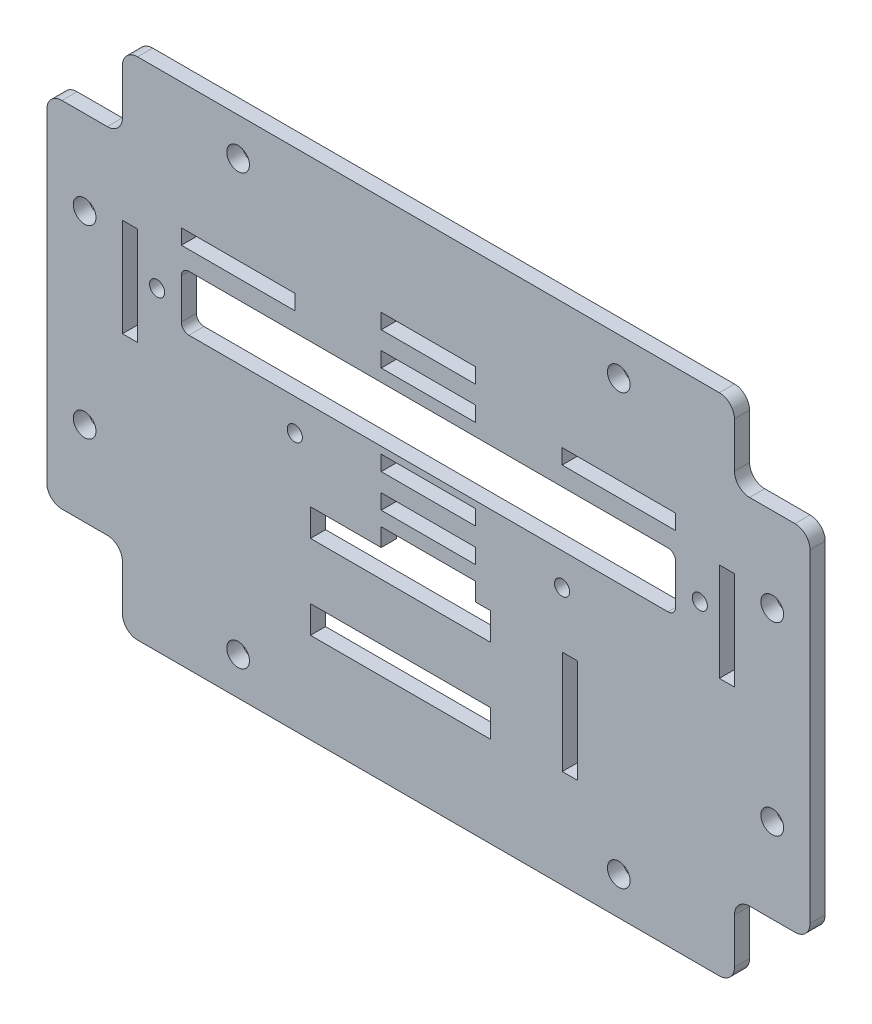
SolidWorks part; units mm, degrees
ref_plane "Front Plane" through (0, 0, 0) normal (0, 0, 1) x (1, 0, 0)
ref_plane "Top Plane" through (0, 0, 0) normal (0, 1, 0) x (1, 0, 0)
ref_plane "Right Plane" through (0, 0, 0) normal (1, 0, 0) x (0, 0, -1)
sketch "Sketch1" plane through (0, 0, 0) normal (0, 0, 1) x (1, 0, 0)
  line L0 (-62.6042, 95.0688) -> (-30.8542, 95.0688)
  line L1 (-30.8542, 95.0688) -> (-30.8542, 100.1488)
  line L2 (-30.8542, 100.1488) -> (-62.6042, 100.1488)
  line L3 (-62.6042, 100.1488) -> (-62.6042, 95.0688)
  line L4 (-62.6042, 106.3017) -> (-30.8542, 106.3017)
  line L5 (-30.8542, 106.3017) -> (-30.8542, 111.3817)
  line L6 (-91.6322, 138.6009) -> (-129.7322, 138.6009)
  line L7 (-144.4697, 135.9652) -> (-144.4697, 127.1956)
  line L8 (-30.8542, 111.3817) -> (-62.6042, 111.3817)
  line L9 (-62.6042, 111.3817) -> (-62.6042, 106.3017)
  line L10 (-62.6042, 141.5187) -> (-62.6042, 136.4387)
  line L11 (-62.6042, 136.4387) -> (-30.8542, 136.4387)
  line L12 (-30.8542, 136.4387) -> (-30.8542, 141.5187)
  line L13 (-162.2497, 132.2748) -> (-162.2497, 94.1323) construction
  line L14 (68.7913, 132.2748) -> (68.7913, 94.1323) construction
  line L15 (-30.8542, 141.5187) -> (-62.6042, 141.5187)
  line L16 (-62.6042, 141.5187) -> (-62.635, 141.5089)
  line L17 (-30.8542, 147.5723) -> (-30.8542, 152.6523)
  line L18 (-75.4947, 173.3689) -> (18.6564, 173.3689) construction
  line L19 (-30.8542, 152.6523) -> (-62.6042, 152.6523)
  line L20 (-1.7677, 84.197) -> (-1.7677, 49.4424)
  line L21 (-62.6042, 152.6523) -> (-62.6042, 147.5723)
  line L22 (-62.6042, 147.5723) -> (-30.8542, 147.5723)
  line L23 (56.0913, 21.4353) -> (56.0913, 36.6753)
  line L24 (-149.5497, 21.4353) -> (-149.5497, 36.6753)
  line L25 (-154.6297, 41.7553) -> (-169.8697, 41.7553)
  line L26 (-144.4697, 186.0689) -> (51.0113, 186.0689)
  line L27 (36.3077, 129.7348) -> (36.3077, 127.1956)
  line L28 (61.1713, 41.7553) -> (76.4113, 41.7553)
  line L29 (81.4913, 101.2121) -> (41.9257, 101.2121) construction
  line L30 (61.1713, 160.6689) -> (76.4113, 160.6689)
  line L31 (56.0913, 180.9889) -> (56.0913, 165.7489)
  line L32 (-25.9222, 49.7003) -> (-25.9222, 55.9976)
  line L33 (33.7677, 132.2748) -> (-127.2261, 132.2748)
  line L34 (-129.7661, 129.7348) -> (-129.7661, 127.1956)
  line L35 (33.7677, 113.6867) -> (-127.2261, 113.6867)
  line L36 (-1.7677, 84.197) -> (3.3123, 84.197)
  line L37 (-149.5497, 180.9889) -> (-149.5497, 165.7489)
  line L38 (-154.6297, 160.6689) -> (-169.8697, 160.6689)
  line L39 (-75.4947, 29.0553) -> (18.6564, 29.0553) construction
  line L40 (-174.9497, 101.2121) -> (-169.8697, 101.2121) construction
  line L41 (-25.9222, 55.9976) -> (-86.3722, 55.9976)
  line L42 (-86.3722, 55.9976) -> (-86.3722, 46.7813)
  line L43 (-86.3722, 46.7813) -> (-25.9222, 46.7813)
  line L44 (-25.9222, 46.7813) -> (-25.9222, 49.7003)
  line L45 (-25.9222, 77.8997) -> (-25.9222, 84.197)
  line L46 (-25.9222, 84.197) -> (-30.8542, 84.197)
  line L47 (-86.3722, 84.197) -> (-86.3722, 74.9807)
  line L48 (-86.3722, 74.9807) -> (-25.9222, 74.9807)
  line L49 (-25.9222, 74.9807) -> (-25.9222, 77.8997)
  line L50 (-62.6042, 84.197) -> (-86.3722, 84.197)
  line L51 (51.0113, 135.9652) -> (51.0113, 127.1956)
  line L52 (-1.8261, 138.6009) -> (36.2739, 138.6009)
  line L54 (-62.6042, 84.197) -> (-62.6042, 90.2559)
  line L55 (-62.6042, 90.2559) -> (-30.8542, 90.2559)
  line L56 (-91.6322, 138.6009) -> (-91.6322, 143.6809)
  line L57 (-129.7322, 138.6009) -> (-129.7322, 143.6809)
  line L58 (-46.7292, 155.5889) -> (-46.7292, 153.1054) construction
  line L59 (-1.8261, 138.6009) -> (-1.8261, 143.6809)
  line L60 (36.2739, 138.6009) -> (36.2739, 143.6809)
  line L61 (-30.8542, 84.197) -> (-30.8542, 90.2559)
  line L66 (-149.5497, 135.9652) -> (-144.4697, 135.9652)
  line L69 (-149.5497, 102.9452) -> (-144.4697, 102.9452)
  line L70 (56.0913, 102.9452) -> (51.0113, 102.9452)
  line L71 (56.0913, 135.9652) -> (51.0113, 135.9652)
  line L72 (-174.9497, 155.5889) -> (-174.9497, 46.8353)
  line L77 (-149.5497, 135.9652) -> (-149.5497, 102.9452)
  line L79 (-129.7322, 143.6809) -> (-91.6322, 143.6809)
  line L80 (-1.7677, 49.4424) -> (3.3123, 49.4424)
  line L82 (-147.6829, 127.1956) -> (60.3007, 127.1956) construction
  line L89 (-1.8261, 143.6809) -> (36.2739, 143.6809)
  line L90 (-144.4697, 127.1956) -> (-144.4697, 102.9452)
  line L91 (-129.7661, 127.1956) -> (-129.7661, 116.2267)
  line L92 (36.3077, 127.1956) -> (36.3077, 116.2267)
  line L93 (51.0113, 127.1956) -> (51.0113, 102.9452)
  line L94 (56.0913, 135.9652) -> (56.0913, 102.9452)
  line L95 (3.3123, 84.197) -> (3.3123, 49.4424)
  line L96 (-144.4697, 16.3553) -> (51.0113, 16.3553)
  line L97 (81.4913, 155.5889) -> (81.4913, 46.8353)
  arc A0 (36.3077, 129.7348) -> (33.7677, 132.2748) centre (33.7677, 129.7348) ccw
  arc A1 (36.3077, 116.2267) -> (33.7677, 113.6867) centre (33.7677, 116.2267) cw
  circle A2 centre (-110.6822, 173.3689) radius 3.81
  circle A3 centre (17.2239, 173.3689) radius 3.81
  arc A4 (-149.5497, 21.4353) -> (-144.4697, 16.3553) centre (-144.4697, 21.4353) ccw
  arc A5 (-169.8697, 41.7553) -> (-174.9497, 46.8353) centre (-169.8697, 46.8353) cw
  arc A6 (-154.6297, 41.7553) -> (-149.5497, 36.6753) centre (-154.6297, 36.6753) cw
  circle A7 centre (-110.6822, 29.0553) radius 3.81
  circle A8 centre (17.2239, 29.0553) radius 3.81
  arc A9 (-127.2261, 113.6867) -> (-129.7661, 116.2267) centre (-127.2261, 116.2267) cw
  arc A10 (-127.2261, 132.2748) -> (-129.7661, 129.7348) centre (-127.2261, 129.7348) ccw
  arc A11 (56.0913, 21.4353) -> (51.0113, 16.3553) centre (51.0113, 21.4353) cw
  circle A12 centre (-162.2497, 132.2748) radius 3.81
  circle A13 centre (-137.9037, 121.9952) radius 2.54
  circle A14 centre (44.4453, 121.9952) radius 2.54
  circle A15 centre (-91.6322, 102.9452) radius 2.54
  circle A16 centre (-1.8261, 102.9452) radius 2.54
  arc A17 (61.1713, 41.7553) -> (56.0913, 36.6753) centre (61.1713, 36.6753) ccw
  arc A18 (76.4113, 41.7553) -> (81.4913, 46.8353) centre (76.4113, 46.8353) ccw
  arc A19 (76.4113, 160.6689) -> (81.4913, 155.5889) centre (76.4113, 155.5889) cw
  arc A20 (61.1713, 160.6689) -> (56.0913, 165.7489) centre (61.1713, 165.7489) cw
  arc A21 (56.0913, 180.9889) -> (51.0113, 186.0689) centre (51.0113, 180.9889) ccw
  arc A22 (-149.5497, 180.9889) -> (-144.4697, 186.0689) centre (-144.4697, 180.9889) cw
  arc A23 (-154.6297, 160.6689) -> (-149.5497, 165.7489) centre (-154.6297, 165.7489) ccw
  arc A24 (-169.8697, 160.6689) -> (-174.9497, 155.5889) centre (-169.8697, 155.5889) ccw
  circle A25 centre (-162.2497, 70.1494) radius 3.81
  circle A26 centre (68.7913, 70.1494) radius 3.81
  circle A27 centre (68.7913, 132.2748) radius 3.81
  point P2 (-69.2896, 138.6009)
  point P3 (-144.4697, 138.6009)
  point P8 (-144.4697, 138.6009)
  point P10 (-144.4697, 100.3095)
  point P29 (56.0913, 141.1409)
  point P30 (53.5513, 143.6809)
  point P33 (-91.6907, 46.8353)
  point P37 (56.0913, 97.7695)
  point P39 (-74.3696, 143.6809)
  point P41 (-1.7677, 46.8353)
  point P43 (3.3123, 92.6895)
  point P47 (-46.7292, 132.2748)
  point P48 (-149.5497, 16.3553)
  point P55 (-46.7292, 113.6867)
  point P60 (3.3123, 44.2953)
  point P62 (-19.0888, 143.6809)
  point P64 (-46.7292, 160.6689)
  point P73 (-149.5497, 41.7553)
  point P80 (-129.7661, 113.6867)
  point P83 (-129.7661, 132.2748)
  point P84 (-149.5497, 97.7695)
  point P86 (-147.0097, 143.6809)
  point P87 (-149.5497, 141.1409)
  point P89 (-1.7677, 46.8353)
  point P90 (-1.7677, 92.6895)
  point P95 (51.0113, 100.3095)
  point P96 (51.0113, 138.6009)
  point P98 (51.0113, 138.6009)
  point P99 (-24.1688, 138.6009)
  point P102 (-24.1688, 155.5889)
  point P103 (-69.2896, 155.5889)
  point P145 (-149.5497, 186.0689)
  dimension "D1" = 2.54
  dimension "D6" = 5.08
  dimension "D7" = 5.08
  dimension "D8" = 7.62
  dimension "D9" = 25.4
  dimension "D13" = 5.08
  dimension "D14" = 5.08
  dimension "D11" = 7.62
  dimension "D3" = 38.1
  dimension "D4" = 12.7
  dimension "D5" = 25.4
  dimension "D10" = 25.4
  dimension "D2" = 12.7
extrude "Boss-Extrude1" add sketch "Sketch1" along normal blind 5.08
